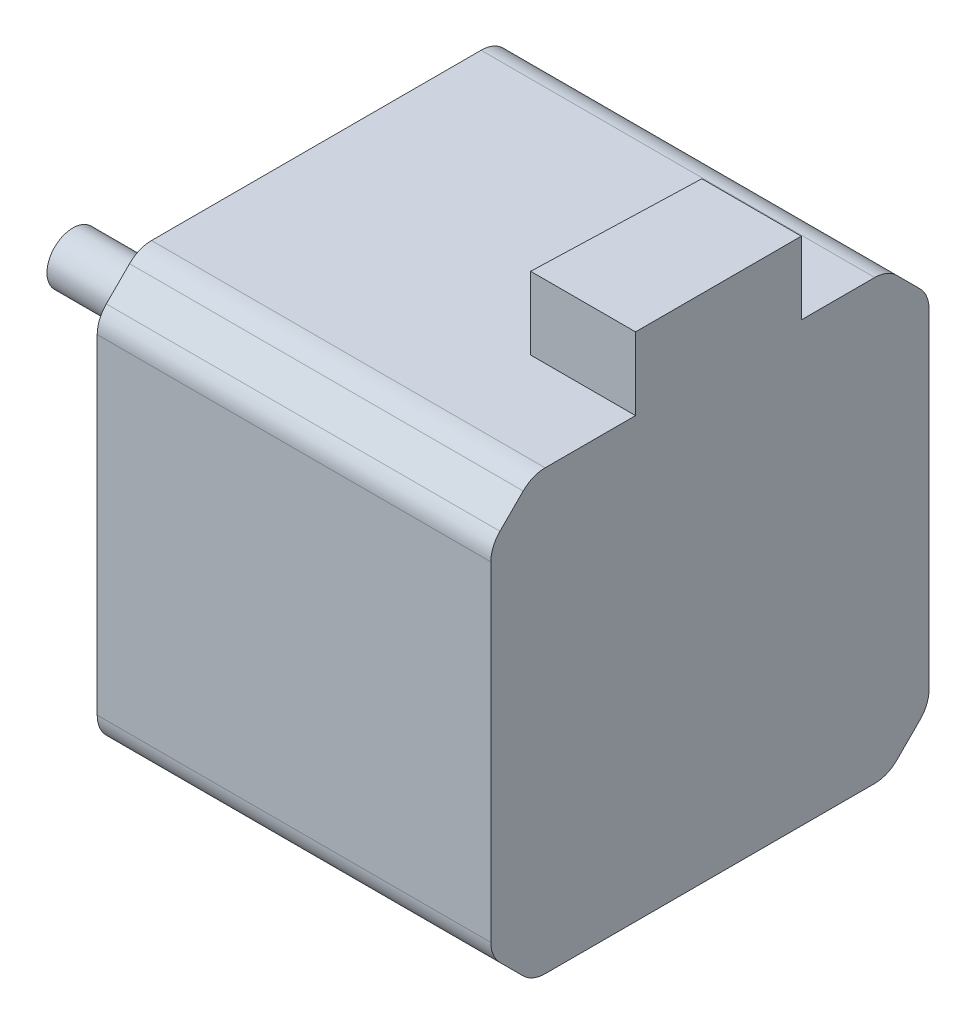
SolidWorks part; units mm, degrees
material "1023 碳钢板 (SS)"
ref_plane "前视基准面" through (0, 0, 0) normal (0, 0, 1) x (1, 0, 0)
ref_plane "上视基准面" through (0, 0, 0) normal (0, 1, 0) x (1, 0, 0)
ref_plane "右视基准面" through (0, 0, 0) normal (1, 0, 0) x (0, 0, -1)
sketch "草图1" plane through (0, 0, 0) normal (1, 0, 0) x (0, 0, -1)
  line L0 (0.8787, 39.1787) -> (3.1213, 41.4213)
  line L1 (5.2426, 0) -> (37.0574, 0)
  line L2 (0, 5.2426) -> (0, 37.0574)
  line L3 (5.2426, 42.3) -> (37.0574, 42.3)
  line L4 (42.3, 5.2426) -> (42.3, 37.0574)
  line L5 (39.1787, 41.4213) -> (41.4213, 39.1787)
  line L6 (0.8787, 3.1213) -> (3.1213, 0.8787)
  line L7 (39.1787, 0.8787) -> (41.4213, 3.1213)
  arc A0 (39.1787, 41.4213) -> (37.0574, 42.3) centre (37.0574, 39.3) ccw
  arc A1 (41.4213, 39.1787) -> (42.3, 37.0574) centre (39.3, 37.0574) cw
  arc A2 (41.4213, 3.1213) -> (42.3, 5.2426) centre (39.3, 5.2426) ccw
  arc A3 (39.1787, 0.8787) -> (37.0574, 0) centre (37.0574, 3) cw
  arc A4 (3.1213, 0.8787) -> (5.2426, 0) centre (5.2426, 3) ccw
  arc A5 (0.8787, 3.1213) -> (0, 5.2426) centre (3, 5.2426) cw
  arc A6 (3.1213, 41.4213) -> (5.2426, 42.3) centre (5.2426, 39.3) cw
  arc A7 (0.8787, 39.1787) -> (0, 37.0574) centre (3, 37.0574) ccw
  point P0 (0, 0)
  point P1 (42.3, 42.3)
  point P2 (0, 42.3)
  point P3 (42.3, 0)
  point P15 (38.3, 42.3)
  point P18 (42.3, 38.3)
  point P21 (42.3, 4)
  point P24 (38.3, 0)
  point P27 (4, 0)
  point P30 (0, 4)
  point P33 (4, 42.3)
  point P36 (0, 38.3)
  dimension "D3" = 3
  dimension "D1" = 42.3
  dimension "D2" = 42.3
extrude "凸台-拉伸2" add sketch "草图1" along normal blind 38 contours L3 A0 L5 A1 L4 A2 L7 A3 L1 A4 L6 A5 L2 A7 L0 A6
sketch "草图2" plane through (0, 0, 0) normal (-1, 0, 0) x (0, 0, 1)
  circle A0 centre (-21.15, 21.15) radius 11
  dimension "D1" = 22
extrude "凸台-拉伸3" add sketch "草图2" along normal blind 2
fillet "圆角1" radius 1 1 edges at (-2, 21.15, -10.15)
sketch "草图3" plane through (-2, 0, 0) normal (-1, 0, 0) x (0, 0, 1)
  circle A0 centre (-21.15, 21.15) radius 2.5
extrude "凸台-拉伸4" add sketch "草图3" along normal blind 21.5 contours A0
sketch "草图4" plane through (0, 0, 0) normal (-1, 0, 0) x (0, 0, 1)
  circle A0 centre (-36.65, 36.65) radius 1.5
  dimension "D1" = 3
  dimension "D2" = 15.5
  dimension "D3" = 15.5
extrude "切除-拉伸1" cut sketch "草图4" against normal blind 4.5
pattern_circular "阵列(圆周)1" count 4 over 360 about axis through (0, 21.15, -21.15) along (1, 0, 0) of "切除-拉伸1"
sketch "草图6" plane through (0, 42.3, 0) normal (0, 1, 0) x (1, 0, 0)
  line L0 (28.4, 29.9675) -> (38, 29.9675)
  line L2 (28.4, 29.9675) -> (27.8726, 13.9675)
  line L3 (38, 5.2426) -> (38, 37.0574) construction
  line L4 (38, 29.9675) -> (38, 13.9675)
  line L5 (38, 13.9675) -> (27.8726, 13.9675)
  dimension "D1" = 16
  dimension "D2" = 9.6
extrude "凸台-拉伸5" add sketch "草图6" along normal blind 7
